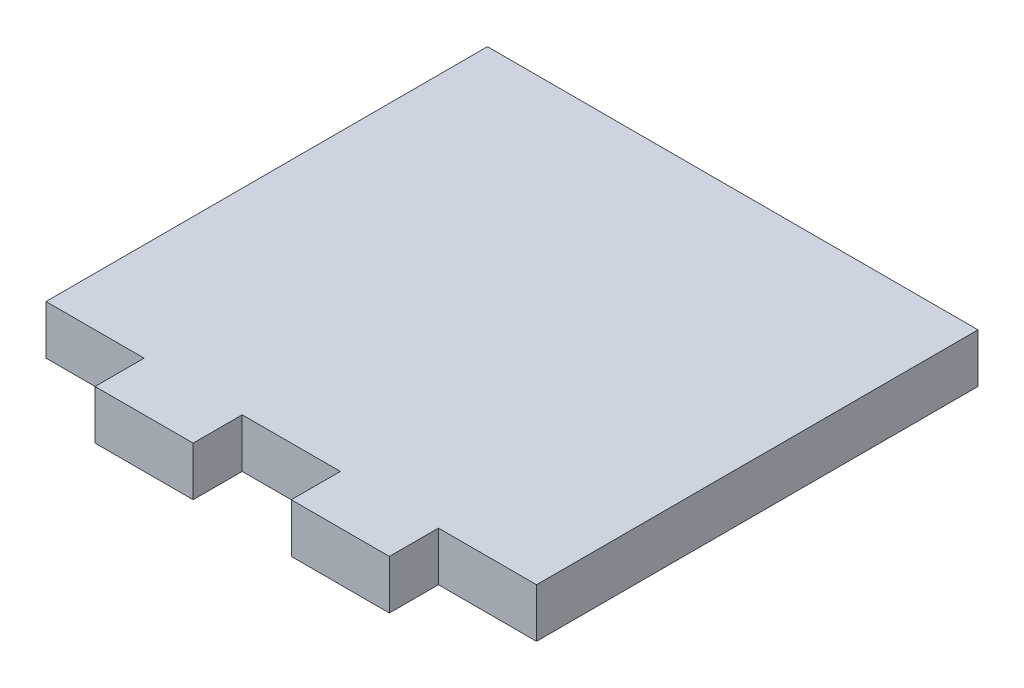
SolidWorks part; units mm, degrees
ref_plane "Front Plane" through (0, 0, 0) normal (0, 0, 1) x (1, 0, 0)
ref_plane "Top Plane" through (0, 0, 0) normal (0, 1, 0) x (1, 0, 0)
ref_plane "Right Plane" through (0, 0, 0) normal (1, 0, 0) x (0, 0, -1)
sketch "Sketch1" plane through (0, 0, 0) normal (0, 1, 0) x (1, 0, 0)
  line L1 (-50, 50) -> (50, 50)
  line L2 (-50, 50) -> (-50, -50)
  line L3 (-50, -50) -> (50, -50)
  line L4 (50, 50) -> (50, -50)
  line L5 (-50, 50) -> (50, -50) construction
  line L6 (-50, -50) -> (50, 50) construction
  point P0 (0, 0)
  dimension "D1" = 100
extrude "Boss-Extrude1" add sketch "Sketch1" along normal blind 10
sketch "Sketch2" plane through (0, 10, 0) normal (0, 1, 0) x (1, 0, 0)
  line L0 (-50, -50) -> (50, -50) construction
  line L1 (-50, -50) -> (-30, -50)
  line L2 (-50, -50) -> (-50, -40)
  line L3 (-50, -40) -> (-30, -40)
  line L4 (-30, -50) -> (-30, -40)
  line L5 (-10, -50) -> (10, -50)
  line L6 (-10, -50) -> (-10, -40)
  line L7 (-10, -40) -> (10, -40)
  line L8 (10, -50) -> (10, -40)
  line L10 (50, -50) -> (30, -50)
  line L11 (50, -50) -> (50, -40)
  line L12 (50, -40) -> (30, -40)
  line L13 (30, -50) -> (30, -40)
extrude "Cut-Extrude1" cut sketch "Sketch2" against normal blind 10
